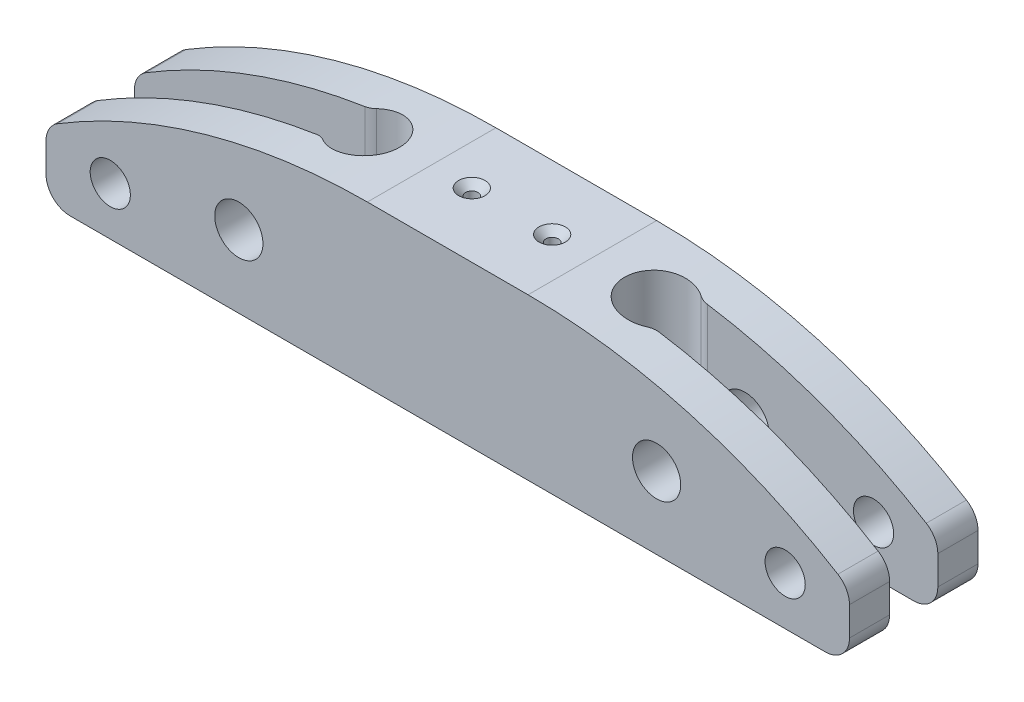
SolidWorks part; units mm, degrees
material "Brass"
ref_plane "Front Plane" through (0, 0, 0) normal (0, 0, 1) x (1, 0, 0)
ref_plane "Top Plane" through (0, 0, 0) normal (0, 1, 0) x (1, 0, 0)
ref_plane "Right Plane" through (0, 0, 0) normal (1, 0, 0) x (0, 0, -1)
sketch "Sketch1" plane through (0, 0, 0) normal (0, 0, 1) x (1, 0, 0)
  line L1 (0, -50) -> (-125, -50)
  line L2 (-125, -50) -> (-125, -29.3562)
  line L3 (-25, 0) -> (-125, 0) construction
  line L4 (-25, 0) -> (0, 0)
  line L5 (0, 0) -> (0, -50)
  arc A0 (-125, -29.3562) -> (-25, 0) centre (-25, -185) cw
  dimension "D4" = 185
  dimension "D1" = 25
  dimension "D2" = 125
  dimension "D3" = 50
extrude "Boss-Extrude1" add sketch "Sketch1" along normal mid plane 40
sketch "Sketch2" plane through (0, 0, 20) normal (0, 0, 1) x (1, 0, 0)
  line L8 (-105, -35) -> (-15, -35)
  line L9 (-15, -35) -> (-15, -15)
  line L10 (-15, -15) -> (-25, -15)
  line L11 (-105, -35) -> (-15, -35) construction
  line L12 (-15, -35) -> (-15, -15) construction
  line L13 (-15, -15) -> (-25, -15) construction
  circle A0 centre (-105, -35) radius 6.25
  circle A1 centre (-65, -27.5) radius 7.5
  arc A4 (-25, -15) -> (-105, -35) centre (-25, -185) ccw
  arc A5 (-25, -15) -> (-105, -35) centre (-25, -185) ccw construction
  point P0 (-61.736, -27.1011)
  point P4 (-104.5085, -34.7389)
  dimension "D1" = 15
  dimension "D2" = 12.5
  dimension "D3" = 15
extrude "Cut-Extrude1" cut sketch "Sketch2" against normal through all
sketch "Sketch3" plane through (0, -50, 0) normal (0, -1, 0) x (-1, 0, 0)
  line L0 (125, -20) -> (125, 20) construction
  line L1 (125, 7.5) -> (45, 7.5)
  line L2 (125, 7.5) -> (125, -7.5)
  line L3 (125, -7.5) -> (45, -7.5)
  line L4 (45, 7.5) -> (45, -7.5)
  line L7 (0, 0) -> (125, 0) construction
  circle A0 centre (45, 0) radius 10
  point P13 (45, 0)
  dimension "D1" = 15
  dimension "D2" = 80
extrude "Cut-Extrude3" cut sketch "Sketch3" against normal through all contours L2 L1 L4 L3 | A0
hole_wizard "CSK for M3.5 Flat Head Machine Screw1" positions "Sketch7" profile "Sketch9" countersink size "M3.5" standard "ANSI Metric" end condition through all
sketch "Sketch7" plane through (0, 0, 0) normal (0, 1, 0) x (1, 0, 0)
  line L0 (-12.5, 20) -> (-12.5, -20) construction
  line L1 (0, 20) -> (-25, 20) construction
  line L2 (0, -20) -> (-25, -20) construction
  point P0 (-12.5, 0)
  point P12 (-12.5, 0)
sketch "Sketch9" plane through (-12.5, 0, 0) normal (1, 0, 0) x (0, 0, 1)
  line L0 (0, 0) -> (0, 50)
  line L1 (0, 50) -> (1.95, 50)
  line L2 (1.95, 50) -> (1.95, 2.15)
  line L3 (1.95, 2.15) -> (4.1, 0)
  line L5 (4.1, 0) -> (0, 0)
  line L6 (-1.95, 2.15) -> (-4.1, 0) construction
  line L11 (0, -6.35) -> (0, 107.95) construction
  dimension "Thru Hole Dia." = 3.9
  dimension "Thru Hole Depth" = 50
  dimension "Near C'Sink Dia." = 8.2
  dimension "Near C'Sink Angle" = 90
fillet "Fillet2" radius 7.5 4 edges at (-125, -50, 13.75) (-125, -29.3562, 13.75) (-125, -50, -13.75) (-125, -29.3562, -13.75)
fillet "Fillet4" radius 5 2 edges at (-51.6144, -25.9622, 7.5) (-51.6144, -25.9622, -7.5)
mirror "Mirror2" about plane through (0, 0, 20) normal (-1, 0, 0) of "Fillet4", "Fillet2", "CSK for M3.5 Flat Head Machine Screw1", "Cut-Extrude3", "Cut-Extrude1", "Boss-Extrude1"
sketch "Sketch13" plane through (0, 0, 0) normal (0, 0, 1) x (1, 0, 0)
  text T0 "J. SHEN, MAE94 - UCLA" font "Century Gothic" height 3.175
